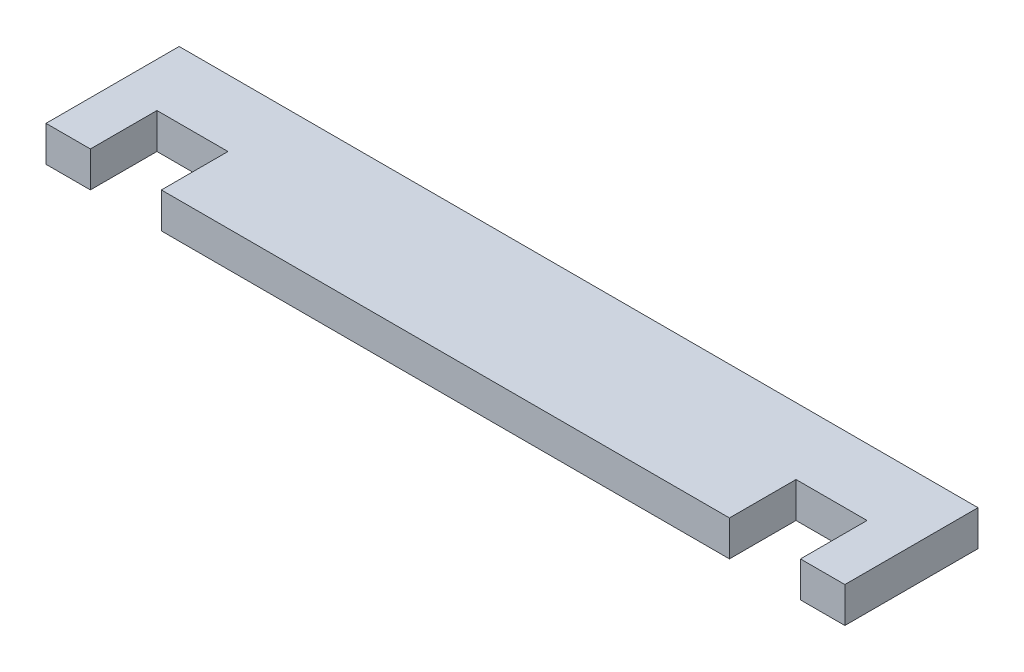
SolidWorks part; units mm, degrees
ref_plane "Front Plane" through (0, 0, 0) normal (0, 0, 1) x (1, 0, 0)
ref_plane "Top Plane" through (0, 0, 0) normal (0, 1, 0) x (1, 0, 0)
ref_plane "Right Plane" through (0, 0, 0) normal (1, 0, 0) x (0, 0, -1)
sketch "Sketch1" plane through (0, 0, 0) normal (0, 1, 0) x (1, 0, 0)
  line L1 (-90, -15) -> (90, -15)
  line L2 (-90, -15) -> (-90, 15)
  line L3 (-90, 15) -> (90, 15)
  line L4 (90, -15) -> (90, 15)
  line L5 (-90, -15) -> (90, 15) construction
  line L6 (-90, 15) -> (90, -15) construction
  point P0 (0, 0)
  dimension "D1" = 180
  dimension "D2" = 30
extrude "Boss-Extrude1" add sketch "Sketch1" along normal blind 8
sketch "Sketch2" plane through (0, 8, 0) normal (0, 1, 0) x (1, 0, 0)
  line L0 (90, 15) -> (-90, 15) construction
  line L3 (-80, -15) -> (80, -15) construction
  line L4 (-80, -15) -> (-80, 15) construction
  line L5 (-80, 15) -> (80, 15) construction
  line L6 (80, -15) -> (80, 15) construction
  line L7 (-80, -15) -> (80, 15) construction
  line L8 (-80, 15) -> (80, -15) construction
  point P0 (0, 0)
  dimension "D1" = 160
sketch "Sketch3" plane through (0, 8, 0) normal (0, 1, 0) x (1, 0, 0)
  line L1 (-80, -15) -> (-64, -15)
  line L2 (-80, -15) -> (-80, 0)
  line L3 (-80, 0) -> (-64, 0)
  line L4 (-64, -15) -> (-64, 0)
  dimension "D1" = 15
  dimension "D2" = 16
extrude "Cut-Extrude1" cut sketch "Sketch3" against normal blind 8
mirror "Mirror1" about plane through (0, 0, 0) normal (1, 0, 0) of "Cut-Extrude1"
